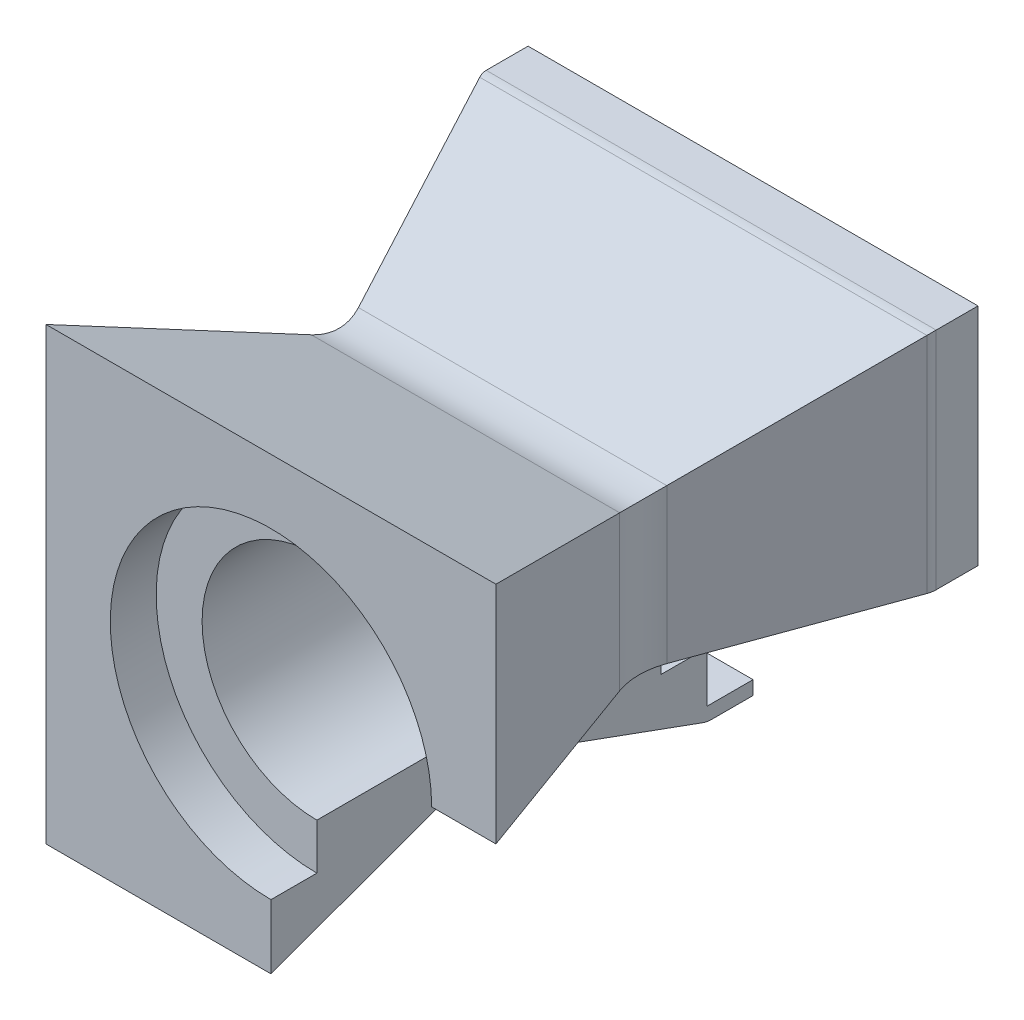
SolidWorks part; units mm, degrees
material "Acier inoxydable moulé"
ref_plane "Plan de face" through (0, 0, 0) normal (0, 0, 1) x (1, 0, 0)
ref_plane "Plan de dessus" through (0, 0, 0) normal (0, 1, 0) x (1, 0, 0)
ref_plane "Plan de droite" through (0, 0, 0) normal (1, 0, 0) x (0, 0, -1)
sketch "Esquisse1" plane through (0, 0, 0) normal (0, 0, 1) x (1, 0, 0)
  line L0 (0, 98) -> (49, 49) construction
  line L1 (0, 0) -> (98, 0)
  line L2 (0, 0) -> (0, 98)
  line L3 (0, 98) -> (98, 98)
  line L4 (98, 0) -> (98, 98)
  line L5 (49, 49) -> (0, 0) construction
  circle A0 centre (49, 49) radius 25
  dimension "D1" = 98
  dimension "D2" = 98
extrude "Boss.-Extru.1" add sketch "Esquisse1" along normal blind 47.5 draft 20 contours L2 L1 L4 L3
sketch "Esquisse2" plane through (0, 0, 0) normal (0, 0, -1) x (-1, 0, 0)
  line L4 (-98, 0) -> (0, 0)
  line L5 (-98, 98) -> (-98, 0)
  line L6 (0, 98) -> (-98, 98)
  line L7 (0, 0) -> (0, 98)
  line L8 (-98, 0) -> (0, 0)
  line L9 (-98, 98) -> (-98, 0)
  line L10 (0, 98) -> (-98, 98)
  line L11 (0, 0) -> (0, 98)
  circle A1 centre (-49, 49) radius 25
  circle A2 centre (-49, 49) radius 25
  dimension "D1" = 0
  dimension "D2" = 0
extrude "Enlèv. mat.-Extru.1" cut sketch "Esquisse2" against normal through all contours A2
mirror "Symétrie1" about plane through (0, 0, 47.5) normal (0, 0, 1) of "Boss.-Extru.1", "Enlèv. mat.-Extru.1"
sketch "Esquisse3" plane through (0, 0, 95) normal (0, 0, 1) x (1, 0, 0)
  line L3 (49, 49) -> (49, 0)
  line L4 (0, 0) -> (98, 0)
  line L5 (98, 0) -> (98, 98)
  line L6 (98, 98) -> (0, 98)
  line L7 (0, 98) -> (0, 0)
  line L8 (0, 0) -> (98, 0)
  line L9 (98, 0) -> (98, 98)
  line L10 (98, 98) -> (0, 98)
  line L11 (0, 98) -> (0, 0)
  line L12 (49, 49) -> (98, 49)
  circle A1 centre (49, 49) radius 25
  circle A2 centre (49, 49) radius 25
  circle M9 centre (49, 49) radius 25
  line M12 (0, 0) -> (98, 0)
  line M13 (98, 0) -> (98, 98)
  dimension "D1" = 0
  dimension "D2" = 0
extrude "Enlèv. mat.-Extru.4" cut sketch "Esquisse3" against normal through all contours L12 L3 M9 M12 M13
fillet "Congé1" radius 15 4 edges at (33.1443, 17.2886, 47.5) (80.7114, 64.8557, 47.5) (49, 80.7114, 47.5) (17.2886, 49, 47.5)
sketch "Esquisse4" plane through (0, 0, 95) normal (0, 0, 1) x (1, 0, 0)
  circle A0 centre (49, 49) radius 35
extrude "Enlèv. mat.-Extru.5" cut sketch "Esquisse4" against normal blind 10
sketch "Esquisse5" plane through (0, 0, 0) normal (0, 0, -1) x (-1, 0, 0)
  circle A0 centre (-49, 49) radius 35
extrude "Enlèv. mat.-Extru.6" cut sketch "Esquisse5" against normal blind 10
sketch "Esquisse6" plane through (0, 0, 0) normal (0, 0, -1) x (-1, 0, 0)
  line L0 (-98, 49) -> (-98, 98) construction
  line L1 (-98, 49) -> (-98, 98)
  line L2 (0, 0) -> (-49, 0) construction
  line L3 (0, 0) -> (0, 98) construction
  line L4 (0, 98) -> (-98, 98) construction
  line L5 (0, 0) -> (-49, 0)
  line L6 (0, 0) -> (0, 98)
  line L7 (0, 98) -> (-98, 98)
  line L8 (-95, 49) -> (-95, 95)
  line L9 (-3, 95) -> (-95, 95)
  line L10 (-3, 3) -> (-3, 95)
  line L11 (-3, 3) -> (-49, 3)
  line L12 (-95, 49) -> (-98, 49)
  line L13 (-49, 3) -> (-49, 0)
  dimension "D1" = 3
extrude "Boss.-Extru.2" add sketch "Esquisse6" along normal blind 10
fillet "Congé2" radius 5 4 edges at (98, 73.5, 0) (49, 98, 0) (24.5, 0, 0) (0, 49, 0)
sketch "Esquisse7" plane through (0, 0, 0) normal (0, 0, -1) x (-1, 0, 0)
  line L0 (-13.6447, 13.6447) -> (-84.3553, 84.3553) construction
  line L1 (-13.6447, 84.3553) -> (-49, 49) construction
  line L2 (-89.6586, 89.6586) -> (-79.052, 79.052) construction
  line L3 (-87.5373, 91.78) -> (-76.9307, 81.1734)
  line L4 (-91.78, 87.5373) -> (-81.1734, 76.9307)
  line L5 (-8.3414, 89.6586) -> (-18.948, 79.052) construction
  line L6 (-6.22, 87.5373) -> (-16.8266, 76.9307)
  line L7 (-10.4627, 91.78) -> (-21.0693, 81.1734)
  line L8 (-8.3414, 8.3414) -> (-18.948, 18.948) construction
  line L9 (-10.4627, 6.22) -> (-21.0693, 16.8266)
  line L10 (-6.22, 10.4627) -> (-16.8266, 21.0693)
  arc A1 (-87.5373, 91.78) -> (-91.78, 87.5373) centre (-89.6586, 89.6586) ccw
  arc A2 (-81.1734, 76.9307) -> (-76.9307, 81.1734) centre (-79.052, 79.052) ccw
  arc A3 (-6.22, 87.5373) -> (-10.4627, 91.78) centre (-8.3414, 89.6586) ccw
  arc A4 (-21.0693, 81.1734) -> (-16.8266, 76.9307) centre (-18.948, 79.052) ccw
  arc A5 (-10.4627, 6.22) -> (-6.22, 10.4627) centre (-8.3414, 8.3414) ccw
  arc A6 (-16.8266, 21.0693) -> (-21.0693, 16.8266) centre (-18.948, 18.948) ccw
  point P2 (-13.6447, 84.3553)
  point P9 (-84.3553, 84.3553)
  point P18 (-13.6447, 13.6447)
  point P25 (0, 0)
  point P26 (0, 0)
  point P27 (0, 0)
  point P28 (0, 0)
  point P29 (0, 0)
  point P30 (0, 0)
  point P31 (0, 0)
  dimension "D1" = 3
  dimension "D4" = 3
  dimension "D5" = 3
  dimension "D2" = 15
  dimension "D3" = 15
  dimension "D6" = 15
  dimension "D7" = 50
  dimension "D8" = 50
  dimension "D9" = 50
extrude "Enlèv. mat.-Extru.7" cut sketch "Esquisse7" against normal blind 10
equation "\"A\"= 95"
equation "\"B\"= 98"
equation "\"C\"= 20"
equation "\"D1@Esquisse1\"=\"B\""
equation "\"D2@Esquisse1\"=\"B\""
equation "\"D3@Boss.-Extru.1\"=\"C\""
equation "\"D1@Boss.-Extru.1\"=\"A\"/2"
